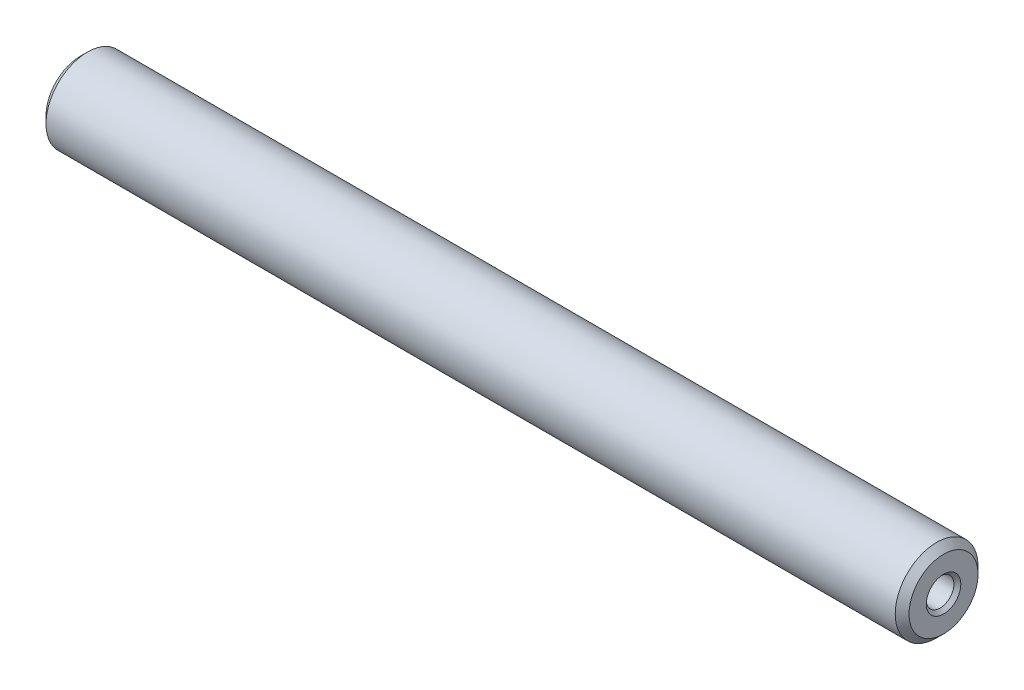
SolidWorks part; units mm, degrees
material "Acier non allié"
ref_plane "Plan de face" through (0, 0, 0) normal (0, 0, 1) x (1, 0, 0)
ref_plane "Plan de dessus" through (0, 0, 0) normal (0, 1, 0) x (1, 0, 0)
ref_plane "Plan de droite" through (0, 0, 0) normal (1, 0, 0) x (0, 0, -1)
sketch "Esquisse1" plane through (0, 0, 0) normal (0, 0, 1) x (1, 0, 0)
  line L0 (-35.683, 0) -> (42.8917, 0) construction
  line L1 (-62.5, 0) -> (-62.5, 6)
  line L2 (-62.5, 6) -> (62.5, 6)
  line L3 (62.5, 6) -> (62.5, 0)
  line L4 (-62.5, 0) -> (62.5, 0)
  dimension "D1" = 125
  dimension "D2" = 62.5
  dimension "D3" = 12
revolve "Révolution1" add sketch "Esquisse1" angle 360 about L0
chamfer "Chanfrein1" distance 1 angle 45 2 edges at (62.5, 0, 6) (-62.5, 0, 6)
hole_wizard "Diamètre du perçage Ø4.0 (4)1" positions "Esquisse3D1" profile "Esquisse2" hole size "Ø4.0" standard "Ansi Métrique"
sketch3d "Esquisse3D1"
  line L0 (61.5, 0, 0) -> (62.5, 0, 0) construction
  line L1 (-61.5, 0, 0) -> (-62.5, 0, 0) construction
  point P0 (62.5, 0, 0)
  point P4 (-62.5, 0, 0)
sketch "Esquisse2" plane through (62.5, 0, 0) normal (0, 1, 0) x (0, 0, -1)
  line L0 (0, 0) -> (0, 12.2017)
  line L1 (0, 12.2017) -> (2, 11)
  line L2 (2, 11) -> (2, 0.5)
  line L3 (2, 0.5) -> (2.5, 0)
  line L5 (2.5, 0) -> (0, 0)
  line L6 (-2, 0.5) -> (-2.5, 0) construction
  line L10 (0, 12.2017) -> (-2, 11) construction
  line L11 (0, -6.35) -> (0, 107.95) construction
  dimension "Diamètre du perçage" = 4
  dimension "Profondeur du perçage" = 11
  dimension "Diamètre du fraisage entrant" = 5
  dimension "Angle du fraisage entrant" = 90
  dimension "Angle de pointe" = 118
